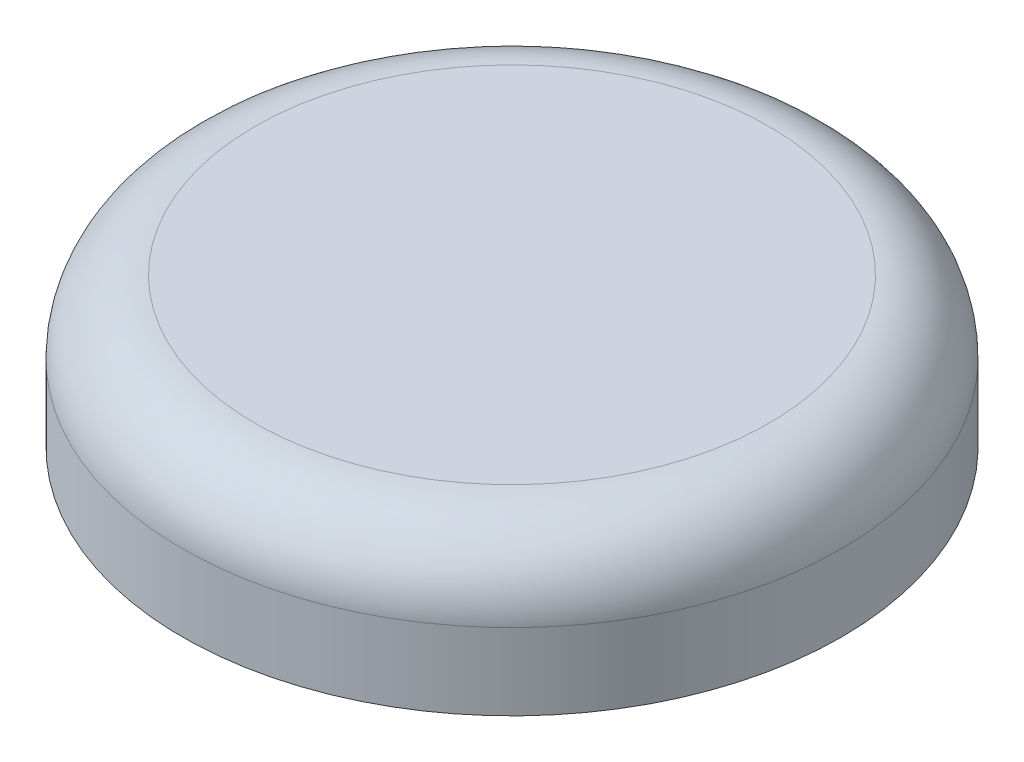
SolidWorks part; units mm, degrees
ref_plane "Front Plane" through (0, 0, 0) normal (0, 0, 1) x (1, 0, 0)
ref_plane "Top Plane" through (0, 0, 0) normal (0, 1, 0) x (1, 0, 0)
ref_plane "Right Plane" through (0, 0, 0) normal (1, 0, 0) x (0, 0, -1)
sketch "Sketch1" plane through (0, 0, 0) normal (0, 0, 1) x (1, 0, 0)
  line L0 (0, 0) -> (0, 2)
  line L1 (0, 2) -> (-19.5, 2)
  line L2 (-25, -3.5) -> (-25, -9.3)
  line L3 (-25, -9.3) -> (-24, -9.3)
  line L4 (-24, -9.3) -> (-24, -4.3)
  line L5 (-24, -4.3) -> (-23, -4.3)
  line L6 (-19.5, 0) -> (0, 0)
  line L7 (0, 0) -> (0, -9.3) construction
  line L8 (0, -9.3) -> (-24, -9.3) construction
  line L9 (-23, -3.5) -> (-23, -4.3)
  line L10 (-25, -9.3) -> (-25, -33.3) construction
  arc A2 (-19.5, 0) -> (-23, -3.5) centre (-19.5, -3.5) ccw
  arc A3 (-19.5, 2) -> (-25, -3.5) centre (-19.5, -3.5) ccw
  dimension "D7" = 11.3
  dimension "D2" = 3.5
  dimension "D1" = 2
  dimension "D3" = 5
  dimension "D4" = 1
  dimension "D5" = 2
revolve "Revolve1" add sketch "Sketch1" angle 360 about L7
